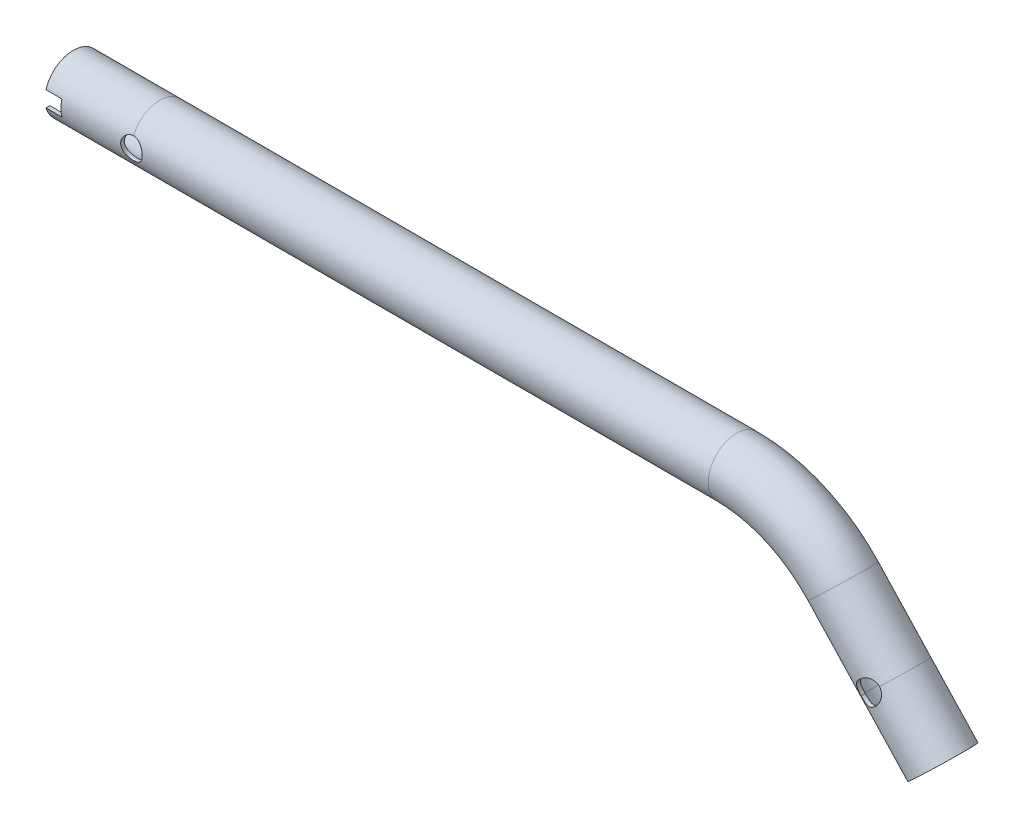
SolidWorks part; units mm, degrees
ref_plane "Front Plane" through (0, 0, 0) normal (0, 0, 1) x (1, 0, 0)
ref_plane "Top Plane" through (0, 0, 0) normal (0, 1, 0) x (1, 0, 0)
ref_plane "Right Plane" through (0, 0, 0) normal (1, 0, 0) x (0, 0, -1)
sketch "Sketch1" plane through (0, 0, 0) normal (0, 0, 1) x (1, 0, 0)
  line L0 (0, 0) -> (188.1072, 0)
  line L1 (222.8465, -15.1051) -> (240, -33.5)
  line L2 (0, 0) -> (-28.2156, 0)
  line L3 (240, -33.5) -> (255.3865, -50)
  arc A0 (222.8465, -15.1051) -> (188.1072, 0) centre (188.1072, -47.5) ccw
  point P10 (240, -33.5)
  dimension "D2" = 47.5
  dimension "D5" = 303
  dimension "D1" = 47
  dimension "D3" = 240
  dimension "D4" = 33.5
  dimension "D6" = 50
ref_plane "Plane1" through (-28.2156, 0, 0) normal (-1, 0, 0) x (0, 0, 1)
sketch "Sketch2" plane through (-28.2156, 0, 0) normal (-1, 0, 0) x (0, 0, 1)
  circle A0 centre (0, 0) radius 9.25
  circle A1 centre (0, 0) radius 8.05
  dimension "D1" = 1.2
  dimension "D2" = 18.5
sweep "Sweep1" add profiles "Sketch2" path "Sketch1"
sketch "Sketch3" plane through (0, 0, 0) normal (0, 0, 1) x (1, 0, 0)
  line L0 (240, -33.5) -> (242.9986, -30.7038) construction
  line L1 (233.235, -39.8085) -> (246.765, -27.1915) construction
  line L2 (240, -33.5) -> (237.5789, -30.9037) construction
  line L3 (243.0555, -30.7649) -> (242.9416, -30.6427)
  line L4 (237.9948, -30.47) -> (237.1172, -31.2883)
  line L5 (236.9445, -36.2351) -> (237.0584, -36.3573)
  line L6 (242.0052, -36.53) -> (242.8828, -35.7117)
  arc A0 (242.0052, -36.53) -> (237.0584, -36.3573) centre (239.6182, -33.9703) cw
  arc A1 (242.8828, -35.7117) -> (243.0555, -30.7649) centre (240.4958, -33.1519) ccw
  arc A2 (242.9416, -30.6427) -> (237.9948, -30.47) centre (240.3818, -33.0297) ccw
  arc A3 (237.1172, -31.2883) -> (236.9445, -36.2351) centre (239.5042, -33.8481) ccw
  point P8 (242.9986, -30.7038)
  point P14 (245.4425, -33.3247)
  point P17 (240.5546, -28.083)
  point P20 (234.5575, -33.6753)
  dimension "D6" = 3.5
  dimension "D1" = 4.1
  dimension "D2" = 3.55
  dimension "D3" = 90
  dimension "D4" = 7.1671
  dimension "D5" = 8.2
extrude "Cut-Extrude1" cut sketch "Sketch3" against normal up to next and the other way up to next
sketch "Sketch4" plane through (0, 0, 0) normal (0, 0, 1) x (1, 0, 0)
  line L0 (0, -9.25) -> (0, 9.25) construction
  circle A0 centre (0, 0) radius 3.5
  dimension "D1" = 7
extrude "Cut-Extrude2" cut sketch "Sketch4" along normal up to next
sketch "Sketch5" plane through (0, 0, 0) normal (0, 0, 1) x (1, 0, 0)
  line L0 (-28.2156, 0) -> (-28.2156, 2.555)
  line L1 (-28.2156, 9.25) -> (-28.2156, -9.25) construction
  line L2 (-28.2156, 2.555) -> (-23.0156, 2.555)
  line L3 (-23.0156, 2.555) -> (-23.0156, -2.555)
  line L4 (-23.0156, -2.555) -> (-28.2156, -2.555)
  line L5 (-28.2156, -2.555) -> (-28.2156, 0)
  dimension "D1" = 5.2
  dimension "D2" = 5.11
extrude "Cut-Extrude3" cut sketch "Sketch5" against normal through all and the other way through all
